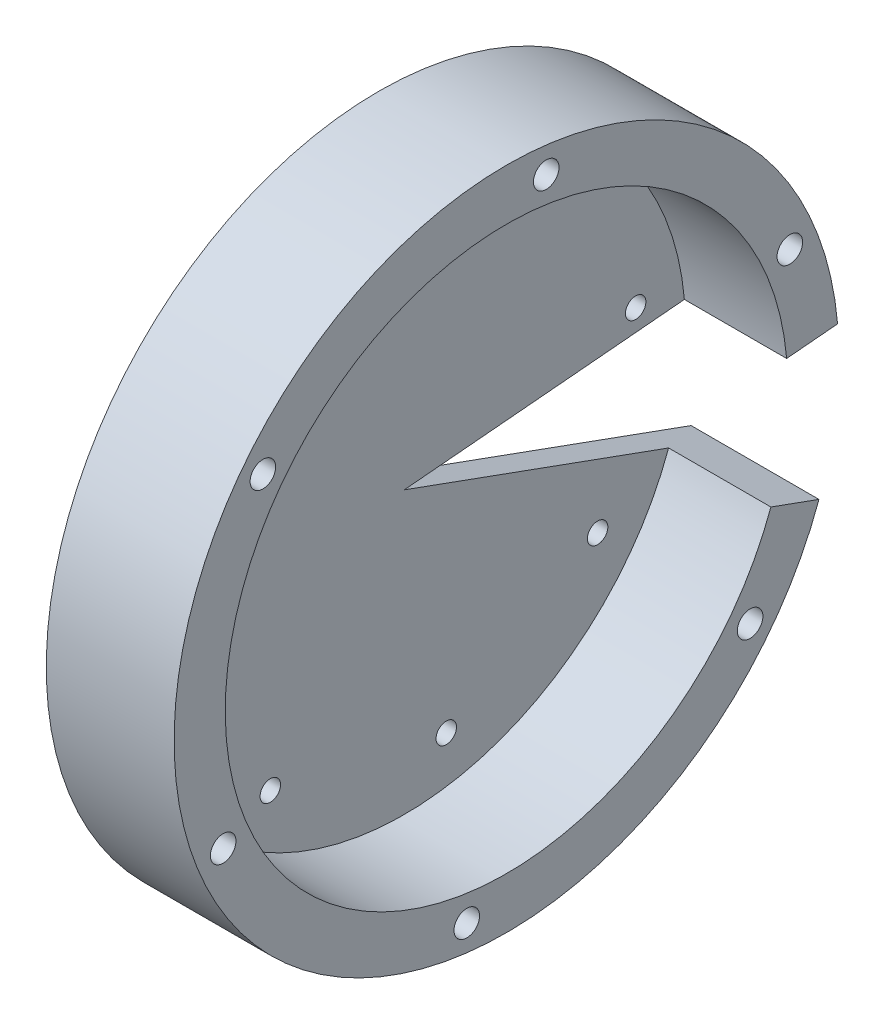
SolidWorks part; units mm, degrees
ref_plane "前视基准面" through (0, 0, 0) normal (0, 0, 1) x (1, 0, 0)
ref_plane "上视基准面" through (0, 0, 0) normal (0, 1, 0) x (1, 0, 0)
ref_plane "右视基准面" through (0, 0, 0) normal (1, 0, 0) x (0, 0, -1)
other "Configuration Table"
sketch "草图1" plane through (0, 0, 0) normal (1, 0, 0) x (0, 0, -1)
  circle A0 centre (0, 0) radius 55
  circle A1 centre (0, 0) radius 65
  circle A2 centre (0, 0) radius 60
  dimension "D1" = 110
  dimension "D2" = 130
  dimension "D3" = 5
extrude "凸台-拉伸1" add sketch "草图1" along normal blind 5 contours A0
sketch "草图2" plane through (0, 0, 0) normal (-1, 0, 0) x (0, 0, 1)
  circle A1 centre (0, 0) radius 60
  circle A2 centre (0, 0) radius 60
  circle A3 centre (0, 0) radius 65
  circle A4 centre (0, 0) radius 65
  circle A5 centre (0, 0) radius 55
  circle A6 centre (0, 0) radius 55
  circle M4 centre (0, 0) radius 55
  dimension "D1" = 0
  dimension "D2" = 0
  dimension "D3" = 0
extrude "凸台-拉伸2" add sketch "草图2" against normal blind 25 contours A2 M4 | A4 A2
sketch "草图3" plane through (0, 0, 0) normal (-1, 0, 0) x (0, 0, 1)
  line L0 (-22.7128, -60.9026) -> (40.1538, 51.1143)
  line L1 (40.1538, 51.1143) -> (22.7128, 60.9026)
  line L2 (22.7128, 60.9026) -> (-40.1538, -51.1143)
  line L3 (-40.1538, -51.1143) -> (-22.7128, -60.9026)
  line L4 (8.6852, -4.956) -> (-8.6852, 4.956)
  circle A0 centre (-7.7679, 59.495) radius 2.5
  circle A1 centre (0, 0) radius 60
  circle A2 centre (0, 0) radius 60
  circle A3 centre (0, 0) radius 65
  circle A4 centre (0, 0) radius 65
  circle A5 centre (0, 0) radius 55
  circle A6 centre (0, 0) radius 55
  circle A7 centre (47.6403, 36.4747) radius 2.5
  circle A8 centre (55.4082, -23.0203) radius 2.5
  circle A9 centre (7.7679, -59.495) radius 2.5
  circle A10 centre (-47.6403, -36.4747) radius 2.5
  circle A11 centre (-55.4082, 23.0203) radius 2.5
  point P23 (0, 0)
  dimension "D4" = 5
  dimension "D6" = 20
  dimension "D7" = 10
  dimension "D1" = 0
  dimension "D2" = 0
  dimension "D3" = 0
  dimension "D5" = 6
extrude "切除-拉伸1" cut sketch "草图3" against normal through all contours A2 A9 | A2 A9 | A0 A2 | A2 A0 | A8 | A10 | A11 | A7
sketch "草图4" plane through (0, 0, 0) normal (-1, 0, 0) x (0, 0, 1)
  circle A0 centre (-7.7679, 59.495) radius 2.5 construction
  circle A1 centre (0, 0) radius 65
  circle A2 centre (0, 0) radius 65
  circle A3 centre (-7.7679, 59.495) radius 2.5
  circle A4 centre (-7.7679, 59.495) radius 4
  circle A5 centre (47.6403, 36.4747) radius 4
  circle A6 centre (55.4082, -23.0203) radius 4
  circle A7 centre (7.7679, -59.495) radius 4
  circle A8 centre (-47.6403, -36.4747) radius 4
  circle A9 centre (-55.4082, 23.0203) radius 4
  point P20 (0, 0)
  dimension "D2" = 8
  dimension "D1" = 0
  dimension "D3" = 6
extrude "切除-拉伸2" cut sketch "草图4" against normal blind 10
sketch "草图5" plane through (0, 0, 0) normal (-1, 0, 0) x (0, 0, 1)
  circle A0 centre (0, 0) radius 46
  circle A1 centre (0, 0) radius 60
  circle A2 centre (0, 0) radius 60
  circle A3 centre (0, 0) radius 65
  circle A4 centre (0, 0) radius 65
  circle A5 centre (0, 0) radius 55
  circle A6 centre (0, 0) radius 55
  circle A7 centre (-26.1874, 37.8182) radius 2
  circle A8 centre (8.2242, 45.2588) radius 2
  circle A9 centre (37.8182, 26.1874) radius 2
  circle A10 centre (45.2588, -8.2242) radius 2
  circle A11 centre (26.1874, -37.8182) radius 2
  circle A12 centre (-8.2242, -45.2588) radius 2
  circle A13 centre (-37.8182, -26.1874) radius 2
  circle A14 centre (-45.2588, 8.2242) radius 2
  point P29 (0, 0)
  dimension "D4" = 92
  dimension "D5" = 4
  dimension "D1" = 0
  dimension "D2" = 0
  dimension "D3" = 0
  dimension "D6" = 8
extrude "切除-拉伸3" cut sketch "草图5" against normal up to next contours A9 | A8 | A7 | A14 | A13 | A12 | A11 | A10
sketch "草图6" plane through (0, 0, 0) normal (-1, 0, 0) x (0, 0, 1)
  circle A0 centre (8.2242, 45.2588) radius 2 construction
  circle A1 centre (0, 0) radius 65
  circle A2 centre (0, 0) radius 65
  circle A3 centre (8.2242, 45.2588) radius 2
  circle A4 centre (8.2242, 45.2588) radius 2.5
  circle A5 centre (37.8182, 26.1874) radius 2
  circle A6 centre (45.2588, -8.2242) radius 2
  circle A7 centre (26.1874, -37.8182) radius 2
  circle A8 centre (-8.2242, -45.2588) radius 2
  circle A9 centre (-37.8182, -26.1874) radius 2
  circle A10 centre (-45.2588, 8.2242) radius 2
  circle A11 centre (-26.1874, 37.8182) radius 2
  circle A12 centre (37.8182, 26.1874) radius 2.5
  circle A13 centre (45.2588, -8.2242) radius 2.5
  circle A14 centre (26.1874, -37.8182) radius 2.5
  circle A15 centre (-8.2242, -45.2588) radius 2.5
  circle A16 centre (-37.8182, -26.1874) radius 2.5
  circle A17 centre (-45.2588, 8.2242) radius 2.5
  circle A18 centre (-26.1874, 37.8182) radius 2.5
  point P24 (0, 0)
  point P39 (0, 0)
  dimension "D2" = 5
  dimension "D1" = 0
  dimension "D3" = 8
  dimension "D4" = 8
extrude "切除-拉伸4" cut sketch "草图6" against normal blind 2 contours A17 | A18 | A4 | A16 | A15 | A14 | A13 | A12
sketch "草图8" plane through (0, 0, 0) normal (-1, 0, 0) x (0, 0, 1)
  line L0 (0, 0) -> (-64.7466, 5.7344)
  line L1 (-64.7466, 5.7344) -> (-61.1038, -22.1659)
  line L2 (-61.1038, -22.1659) -> (0, 0)
  line L3 (-55.4082, 23.0203) -> (-47.6403, -36.4747)
  circle A0 centre (0, 0) radius 65 construction
  circle A1 centre (-47.6403, -36.4747) radius 4 construction
  circle A2 centre (0, 0) radius 65
  circle A3 centre (0, 0) radius 65
  circle A4 centre (-55.4082, 23.0203) radius 4 construction
  circle A5 centre (-47.6403, -36.4747) radius 4
  circle A6 centre (-55.4082, 23.0203) radius 4
  circle M18 centre (0, 0) radius 65
  dimension "D1" = 25
  dimension "D2" = 0
extrude "切除-拉伸5" cut sketch "草图8" against normal through all contours L1 M18 | L1 L2 L0
